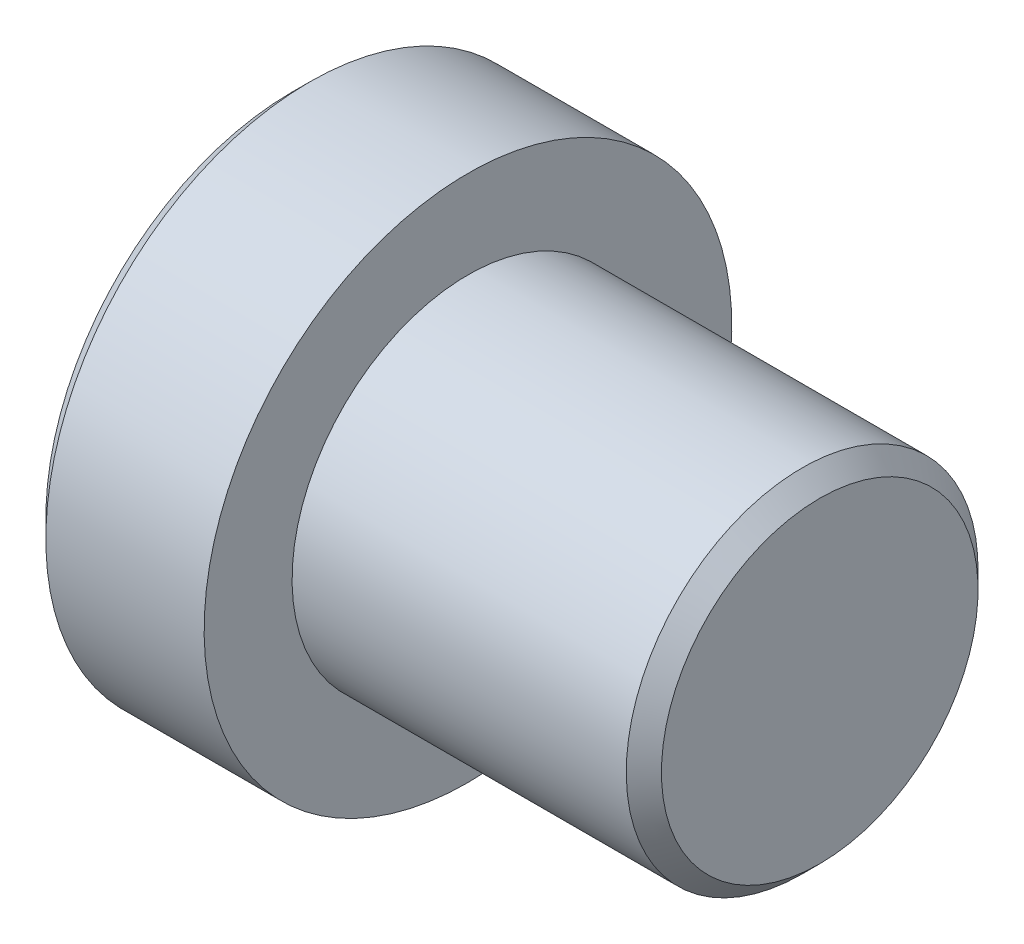
SolidWorks part; units mm, degrees
material "AISI 4130 Steel, normalized at 870C"
ref_plane "Front Plane" through (0, 0, 0) normal (0, 0, 1) x (1, 0, 0)
ref_plane "Top Plane" through (0, 0, 0) normal (0, 1, 0) x (1, 0, 0)
ref_plane "Right Plane" through (0, 0, 0) normal (1, 0, 0) x (0, 0, -1)
sketch "Sketch1" plane through (0, 0, 0) normal (0, 0, 1) x (1, 0, 0)
  line L0 (0, 0) -> (0, 3)
  line L1 (0, 3) -> (2, 3)
  line L2 (2, 3) -> (2, 2)
  line L3 (2, 2) -> (6, 2)
  line L4 (6, 2) -> (6, 0)
  line L5 (6, 0) -> (0, 0)
  line L6 (0, 0) -> (11.8242, 0) construction
  dimension "D1" = 4
  dimension "D2" = 2
  dimension "D3" = 2
  dimension "D4" = 3
revolve "Revolve1" add sketch "Sketch1" angle 360 about L6
cosmetic thread "Cosmetic Thread1" parameters "D2"=3.22
sketch "Sketch2" plane through (0, 0, 0) normal (-1, 0, 0) x (0, 0, 1)
  line L0 (0, 0) -> (0, 2) construction
  line L1 (0, 2) -> (-1.7321, 1)
  line L2 (-1.7321, 1) -> (-1.7321, -1)
  line L3 (-1.7321, -1) -> (0, -2)
  line L4 (0, -2) -> (1.7321, -1)
  line L5 (1.7321, -1) -> (1.7321, 1)
  line L6 (1.7321, 1) -> (0, 2)
  line L7 (0, 0) -> (1.7321, 1) construction
  circle A0 centre (0, 0) radius 1.7321 construction
  dimension "D1" = 2
extrude "Cut-Extrude1" cut sketch "Sketch2" against normal blind 1.5
chamfer "Chamfer1" distance 0.2 angle 45 2 edges at (0, -3, 0) (6, -2, 0)
